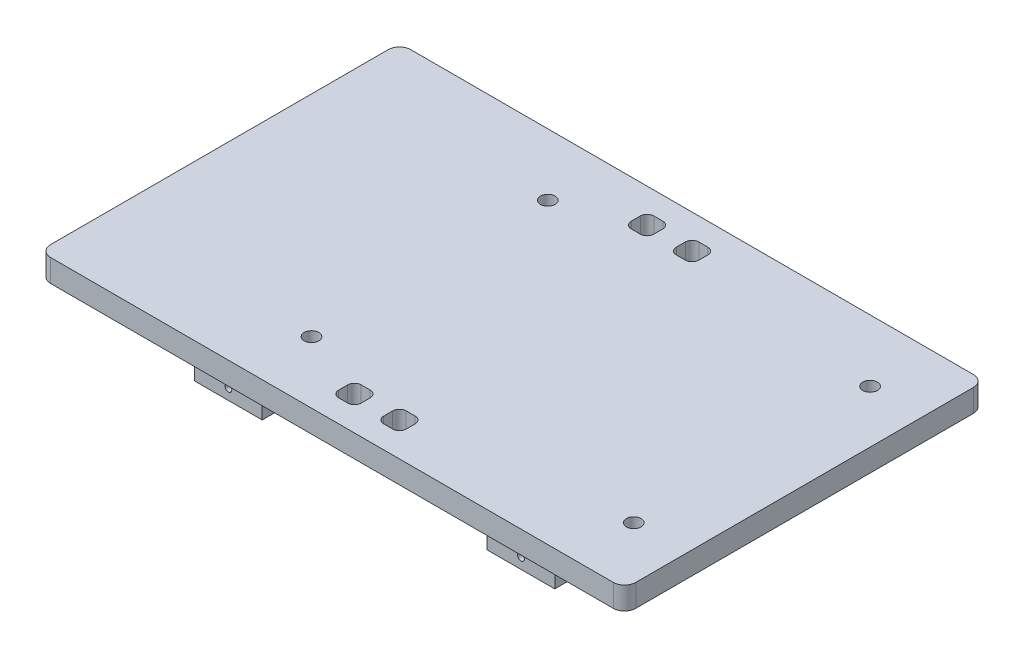
SolidWorks part; units mm, degrees
ref_plane "Front Plane" through (0, 0, 0) normal (0, 0, 1) x (1, 0, 0)
ref_plane "Top Plane" through (0, 0, 0) normal (0, 1, 0) x (1, 0, 0)
ref_plane "Right Plane" through (0, 0, 0) normal (1, 0, 0) x (0, 0, -1)
sketch "Sketch1" plane through (0, 0, 0) normal (0, 1, 0) x (1, 0, 0)
  line L1 (-130, 80) -> (130, 80)
  line L2 (-130, 80) -> (-130, -80)
  line L3 (-130, -80) -> (130, -80)
  line L4 (130, 80) -> (130, -80)
  line L5 (-130, 80) -> (130, -80) construction
  line L6 (-130, -80) -> (130, 80) construction
  point P0 (0, 0)
  dimension "D1" = 260
  dimension "D2" = 160
extrude "Boss-Extrude1" add sketch "Sketch1" along normal blind 10
sketch "Sketch2" plane through (0, 0, 0) normal (0, -1, 0) x (1, 0, 0)
  line L0 (-130, 80) -> (130, 80) construction
  line L1 (-80, 80) -> (-50, 80)
  line L2 (-80, 80) -> (-80, 61) construction
  line L3 (-80, 61) -> (-50, 61)
  line L4 (-50, 80) -> (-50, 61) construction
  line L5 (-130, -80) -> (-130, 80) construction
  line L6 (0, 0) -> (0, 80) construction
  line L7 (-80, 61) -> (-50, 61)
  line L8 (-80, 61) -> (-80, 51)
  line L9 (-80, 51) -> (-50, 51)
  line L10 (-50, 61) -> (-50, 51)
  line L11 (-50, -61) -> (-50, -51)
  line L12 (-130, 0) -> (130, 0) construction
  line L13 (130, 80) -> (130, -80) construction
  line L14 (-80, -51) -> (-50, -51)
  line L15 (-80, -61) -> (-80, -51)
  line L16 (-80, -61) -> (-50, -61)
  line L17 (80, -61) -> (50, -61)
  line L18 (80, -61) -> (80, -51)
  line L19 (80, -51) -> (50, -51)
  line L20 (50, -61) -> (50, -51)
  line L21 (80, 51) -> (50, 51)
  line L22 (50, 61) -> (50, 51)
  line L23 (80, 61) -> (50, 61)
  line L24 (80, 61) -> (80, 51)
  dimension "D1" = 19
  dimension "D2" = 30
  dimension "D3" = 50
  dimension "D4" = 10
extrude "Boss-Extrude2" add sketch "Sketch2" along normal blind 22 contours L10 L3 L8 L9 | L24 L23 L22 L21 | L20 L17 L18 L19 | L15 L16 L11 L14
sketch "Sketch3" plane through (0, 0, 61) normal (0, 0, 1) x (1, 0, 0)
  line L0 (-65, 0) -> (-65, -22) construction
  line L1 (-80, 0) -> (-50, 0) construction
  line L2 (-80, -22) -> (-50, -22) construction
  line L3 (-80, -11) -> (-50, -11) construction
  line L4 (-80, -22) -> (-80, 0) construction
  line L5 (-50, -22) -> (-50, 0) construction
  line L6 (0, 0) -> (0, -22) construction
  circle A0 centre (-65, -2.25) radius 1.5
  circle A1 centre (-65, -19.75) radius 1.5
  circle A2 centre (65, -19.75) radius 1.5
  circle A3 centre (65, -2.25) radius 1.5
  dimension "D1" = 3
  dimension "D2" = 8.75
extrude "Cut-Extrude1" cut sketch "Sketch3" against normal up to surface (112 mm away)
mirror "Mirror1" about plane through (0, 0, 0) normal (0, 0, 1) of "Cut-Extrude1"
sketch "Sketch4" plane through (0, 0, 61) normal (0, 0, 1) x (1, 0, 0)
  line L0 (0, 0) -> (0, -19.1254) construction
  line L1 (-80, -22) -> (-50, -22)
  line L2 (-80, -22) -> (-80, -24.5194)
  line L3 (-80, -24.5194) -> (-50, -24.5194)
  line L4 (-50, -22) -> (-50, -24.5194)
  line L5 (80, -24.5194) -> (50, -24.5194)
  line L6 (50, -22) -> (50, -24.5194)
  line L7 (80, -22) -> (50, -22)
  line L8 (80, -22) -> (80, -24.5194)
extrude "Boss-Extrude3" add sketch "Sketch4" against normal blind 10
mirror "Mirror3" about plane through (0, 0, 0) normal (0, 0, 1) of "Boss-Extrude3"
sketch "Sketch5" plane through (0, 10, 0) normal (0, 1, 0) x (1, 0, 0)
  circle A0 centre (-36.5935, 52.5) radius 3.25
  circle A1 centre (106.5935, 52.5) radius 3.25
  circle A2 centre (-36.5935, -52.5) radius 3.25
  circle A3 centre (106.5935, -52.5) radius 3.25
  dimension "D1" = 6.5
  dimension "D2" = 6.5
  dimension "D3" = 6.5
  dimension "D4" = 6.5
extrude "Cut-Extrude4" cut sketch "Sketch5" against normal blind 10
sketch "Sketch7" plane through (0, 10, 0) normal (0, 1, 0) x (1, 0, 0)
  line L0 (130, 80) -> (-130, 80) construction
  line L1 (-10, 70) -> (0, 70)
  line L2 (-10, 70) -> (-10, 60)
  line L3 (-10, 60) -> (0, 60)
  line L4 (20, 70) -> (20, 60)
  line L5 (130, -80) -> (130, 80) construction
  line L6 (10, 70) -> (10, 60)
  line L7 (0, 60) -> (0, 70)
  line L8 (10, 60) -> (20, 60)
  line L9 (10, 70) -> (20, 70)
  dimension "D1" = 10
  dimension "D2" = 10
  dimension "D3" = 30
  dimension "D4" = 110
  dimension "D5" = 10
  dimension "D6" = 10
extrude "Cut-Extrude5" cut sketch "Sketch7" against normal up to surface (10 mm away) up to face at (106.5935, 0, -49.25)
ref_plane "Plane1" through (0, 0, 0) normal (0, 0, -1) x (-1, 0, 0)
mirror "Mirror4" about plane through (0, 0, 0) normal (0, 0, -1) of "Cut-Extrude5"
fillet "Fillet1" radius 5 4 edges at (130, 5, 80) (130, 5, -80) (-130, 5, -80) (-130, 5, 80)
fillet "Fillet2" radius 3 16 edges at (10, 5, 70) (10, 5, 60) (20, 5, 70) (20, 5, 60) (-10, 5, 70) (0, 5, 70) (0, 5, 60) (-10, 5, 60) (10, 5, -60) (0, 5, -60) (-10, 5, -60) (10, 5, -70) (-10, 5, -70) (0, 5, -70) (20, 5, -60) (20, 5, -70)
